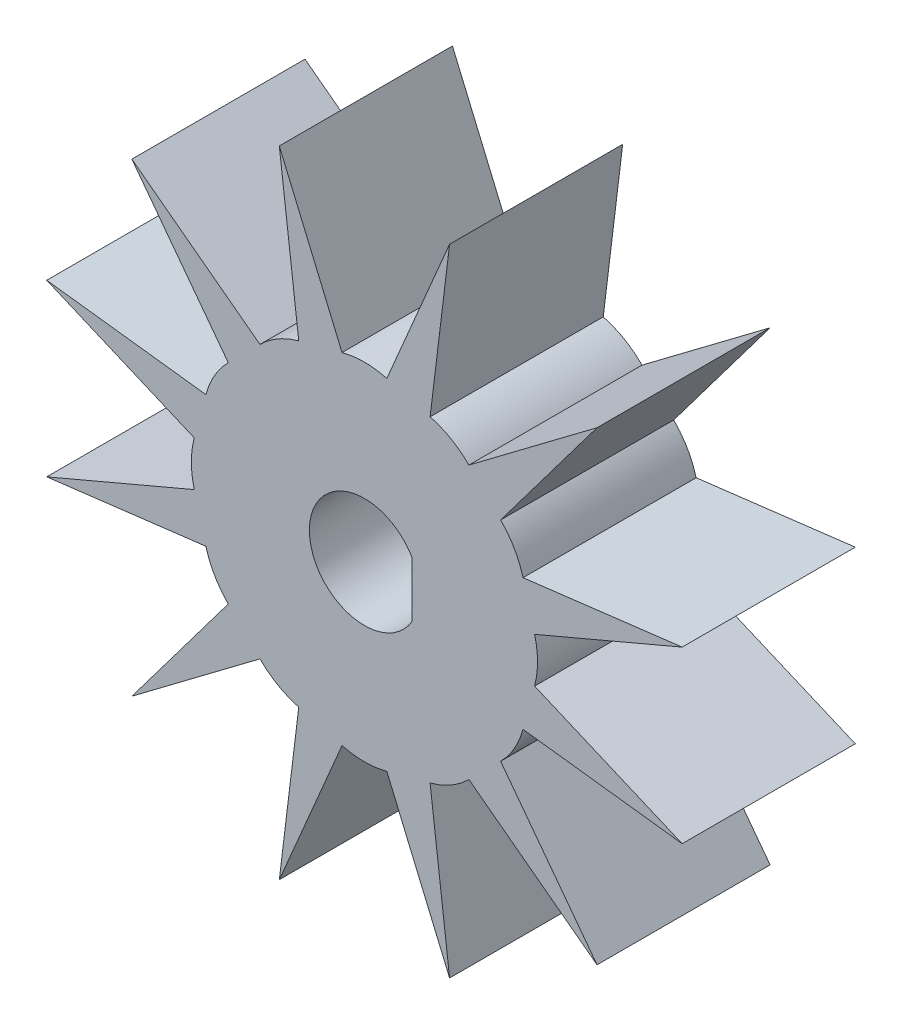
SolidWorks part; units mm, degrees
ref_plane "Front Plane" through (0, 0, 0) normal (0, 0, 1) x (1, 0, 0)
ref_plane "Top Plane" through (0, 0, 0) normal (0, 1, 0) x (1, 0, 0)
ref_plane "Right Plane" through (0, 0, 0) normal (1, 0, 0) x (0, 0, -1)
ref_plane "centerPlane" through (0, 0, 8) normal (0, 0, 1) x (1, 0, 0)
sketch "Sketch2" plane through (0, 0, 8) normal (0, 0, 1) x (1, 0, 0)
  circle A0 centre (25, 25) radius 19
  dimension "D1" = 38
extrude "BaseCircle" add sketch "Sketch2" along normal mid plane 10
ref_point "Point1"
sketch "Sketch4" plane through (0, 0, 13) normal (0, 0, 1) x (1, 0, 0)
  line L0 (27.754, 26.59) -> (27.754, 23.41)
  arc A0 (27.754, 26.59) -> (27.754, 23.41) centre (25, 25) ccw
  dimension "D1" = 3.18
  dimension "D2" = 3.18
extrude "Cut-Extrude2" cut sketch "Sketch4" against normal blind 8
sketch "Sketch3" plane through (0, 0, 13) normal (0, 0, 1) x (1, 0, 0)
  line L0 (20.0824, 6.6474) -> (23.7059, 15.1704)
  line L1 (29.9176, 6.6474) -> (26.2941, 15.1704)
  arc A0 (29.9176, 6.6474) -> (20.0824, 6.6474) centre (25, 25) cw
  arc A1 (23.7059, 15.1704) -> (26.2941, 15.1704) centre (25, 20) ccw
  circle A2 centre (25, 25) radius 19 construction
  point P6 (25, 15)
  point P7 (25, 6)
  dimension "D2" = 19
  dimension "D3" = 5
  dimension "D5" = 30
  dimension "D1" = 5
  dimension "D4" = 30
extrude "Cut-Extrude1" cut sketch "Sketch3" against normal blind 10
pattern_circular "CirPattern1" count 12 over 360 about axis through (25, 25, 0) along (0, 0, 1) of "Cut-Extrude1"
